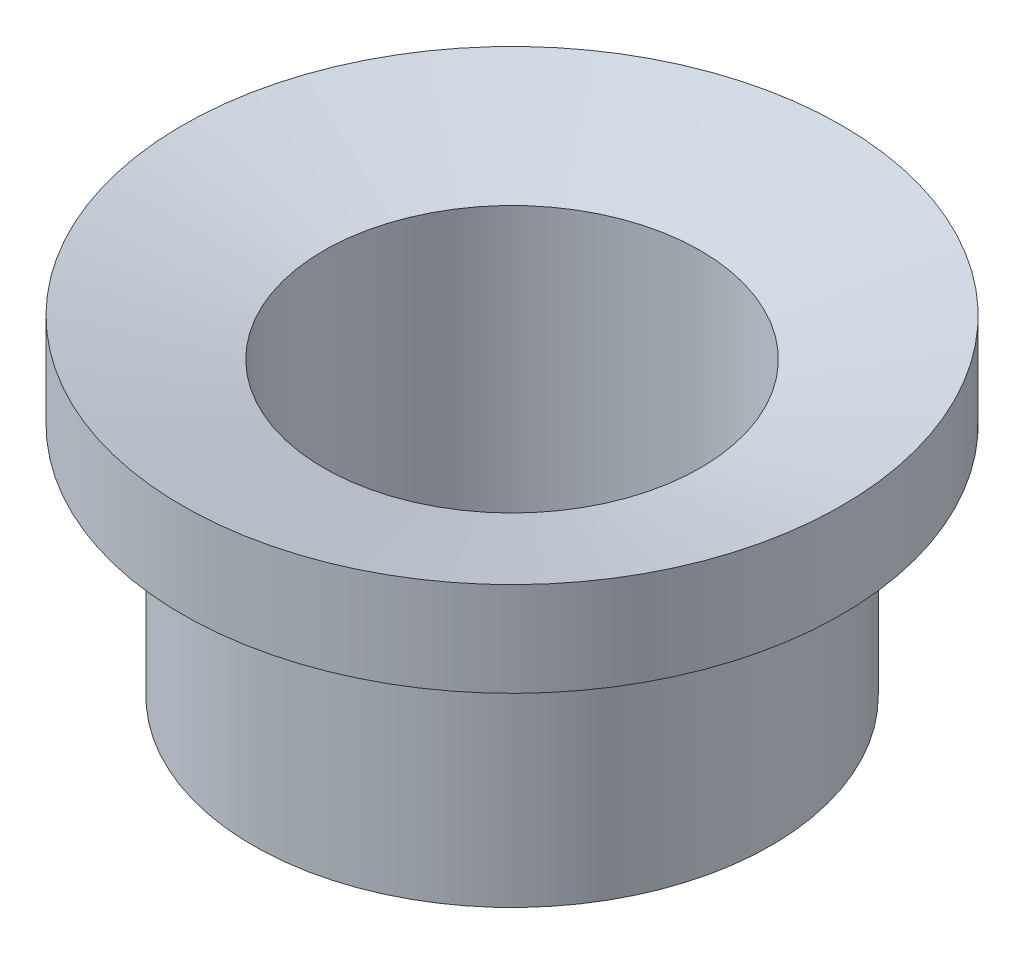
SolidWorks part; units mm, degrees
material "Brass"
ref_plane "Front Plane" through (0, 0, 0) normal (0, 0, 1) x (1, 0, 0)
ref_plane "Top Plane" through (0, 0, 0) normal (0, 1, 0) x (1, 0, 0)
ref_plane "Right Plane" through (0, 0, 0) normal (1, 0, 0) x (0, 0, -1)
sketch "Sketch2" plane through (0, 0, 0) normal (0, 0, 1) x (1, 0, 0)
  line L0 (0, 0) -> (0, 86.1515) construction
  line L1 (12, 0) -> (16.5, 0)
  line L2 (16.5, 0) -> (16.5, 15)
  line L3 (16.5, 15) -> (21, 15)
  line L4 (21, 15) -> (21, 21)
  line L6 (12, 18.5885) -> (12, 0)
  line L7 (12, 18.5885) -> (21, 21)
  dimension "D1" = 15
  dimension "D2" = 6
  dimension "D3" = 21
  dimension "D4" = 16.5
  dimension "D6" = 15
revolve "Revolve1" add sketch "Sketch2" angle 360 about L0
